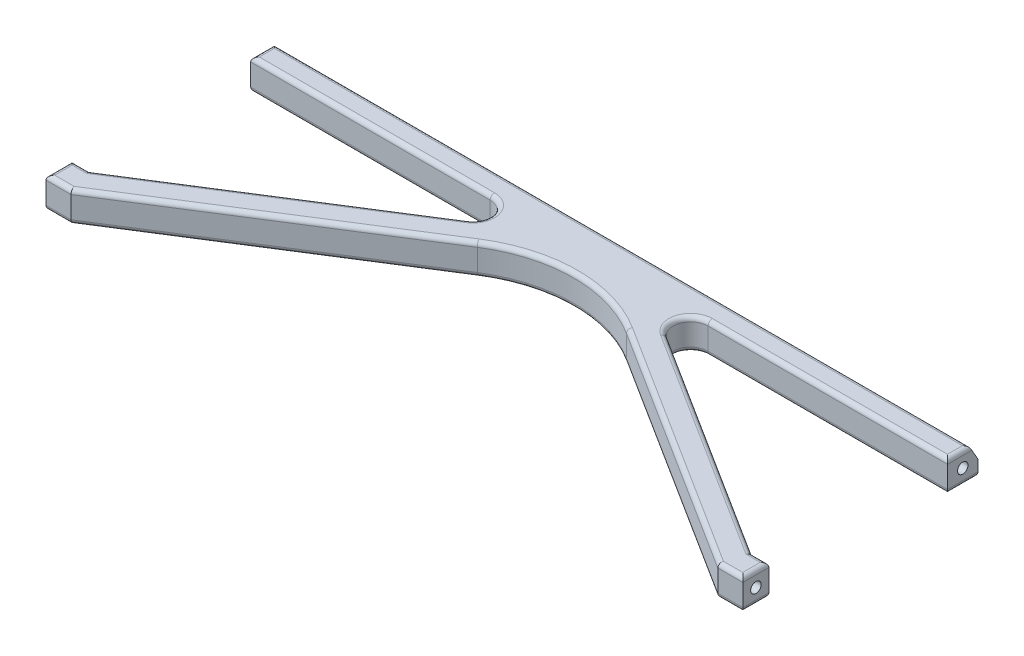
SolidWorks part; units mm, degrees
ref_plane "Front Plane" through (0, 0, 0) normal (0, 0, 1) x (1, 0, 0)
ref_plane "Top Plane" through (0, 0, 0) normal (0, 1, 0) x (1, 0, 0)
ref_plane "Right Plane" through (0, 0, 0) normal (1, 0, 0) x (0, 0, -1)
sketch "Sketch1" plane through (0, 0, 0) normal (0, 1, 0) x (1, 0, 0)
  line L0 (-127, 0) -> (127, 0)
  line L1 (-127, 0) -> (-127, -11.1125)
  line L2 (-127, -11.1125) -> (-55.5274, -11.1125)
  line L3 (-55.5274, -11.1125) -> (-17.8106, -11.1125)
  line L4 (-17.8106, -11.1125) -> (-120.65, -76.2)
  line L5 (-120.65, -76.2) -> (-127, -76.2)
  line L6 (-127, -76.2) -> (-127, -85.725)
  line L7 (-127, -85.725) -> (-117.889, -85.725)
  line L8 (-117.889, -85.725) -> (0, -11.1125)
  line L9 (0, -11.1125) -> (117.889, -85.725)
  line L10 (117.889, -85.725) -> (127, -85.725)
  line L11 (127, -85.725) -> (127, -76.2)
  line L12 (127, -76.2) -> (120.65, -76.2)
  line L13 (120.65, -76.2) -> (17.8106, -11.1125)
  line L14 (17.8106, -11.1125) -> (127, -11.1125)
  line L15 (127, -11.1125) -> (127, 0)
  point P4 (0, 0)
  point P16 (0, 0)
  point P20 (0, -12.7)
  point P21 (-113.6244, -85.725)
  point P22 (-119.9916, -76.2)
  point P23 (17.7527, -12.7)
  point P24 (-116.742, -85.725)
  dimension "D1" = 9.525
  dimension "D2" = 254
  dimension "D3" = 11.1125
  dimension "D4" = 9.525
  dimension "D5" = 76.2
  dimension "D6" = 6.35
extrude "Boss-Extrude1" add sketch "Sketch1" along normal blind 11.1125
chamfer "Chamfer1" distance 3.175 angle 60 1 edges at (0, 11.1125, 0)
fillet "Fillet1" radius 50.8 1 edges at (0, 5.5562, 11.1125)
fillet "Fillet2" radius 6.35 2 edges at (17.8106, 5.5562, 11.1125) (-17.8106, 5.5562, 11.1125)
sketch "Sketch2" plane through (-127, 0, 0) normal (-1, 0, 0) x (0, 0, 1)
  line L0 (0, 0) -> (11.1125, 11.1125) construction
  line L1 (76.2, 0) -> (85.725, 11.1125) construction
  circle A0 centre (5.5562, 5.5562) radius 1.905
  circle A1 centre (80.9625, 5.5562) radius 1.905
  point P12 (5.5562, 5.5562)
  point P13 (80.9625, 5.5562)
  dimension "D1" = 3.81
extrude "Cut-Extrude1" cut sketch "Sketch2" against normal blind 12.7
mirror "Mirror1" about plane through (0, 0, 0) normal (1, 0, 0) of "Cut-Extrude1"
fillet "Fillet4" radius 1.5875 37 edges at (-123.825, 0, 76.2) (-127, 0, 80.9625) (-122.4445, 0, 85.725) (-72.5283, 0, 57.016) (0, 0, 20.4321) (72.5283, 0, 57.016) (122.4445, 0, 85.725) (127, 0, 80.9625) (123.825, 0, 76.2) (78.4858, 0, 49.5141) (33.6185, 0, 15.6946) (83.3587, 0, 11.1125) (127, 0, 5.5562) (0, 0, 0) (-127, 0, 5.5562) (-83.3587, 0, 11.1125) (-33.6185, 0, 15.6946) (-78.4858, 0, 49.5141) (83.3587, 11.1125, 11.1125) (33.6185, 11.1125, 15.6946) (78.4858, 11.1125, 49.5141) (123.825, 11.1125, 76.2) (127, 11.1125, 80.9625) (122.4445, 11.1125, 85.725) (72.5283, 11.1125, 57.016) (0, 11.1125, 20.4321) (-72.5283, 11.1125, 57.016) (-122.4445, 11.1125, 85.725) (-127, 11.1125, 80.9625) (-123.825, 11.1125, 76.2) (-78.4858, 11.1125, 49.5141) (-33.6185, 11.1125, 15.6946) (-83.3587, 11.1125, 11.1125) (-127, 11.1125, 7.1438) (0, 11.1125, 3.175) (127, 11.1125, 7.1437) (0, 5.6132, 0)
